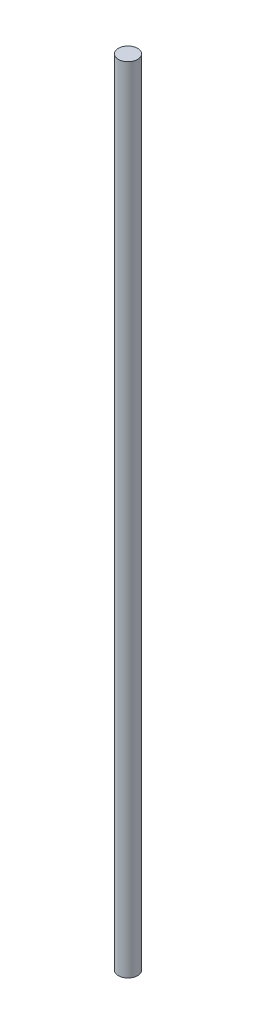
SolidWorks part; units mm, degrees
material "Plain Carbon Steel"
ref_plane "Front Plane" through (0, 0, 0) normal (0, 0, 1) x (1, 0, 0)
ref_plane "Top Plane" through (0, 0, 0) normal (0, 1, 0) x (1, 0, 0)
ref_plane "Right Plane" through (0, 0, 0) normal (1, 0, 0) x (0, 0, -1)
sketch "Sketch1" plane through (0, 0, 0) normal (0, 1, 0) x (1, 0, 0)
  circle A0 centre (0, 0) radius 4
  dimension "D1" = 8
extrude "Boss-Extrude1" add sketch "Sketch1" along normal mid plane 330
